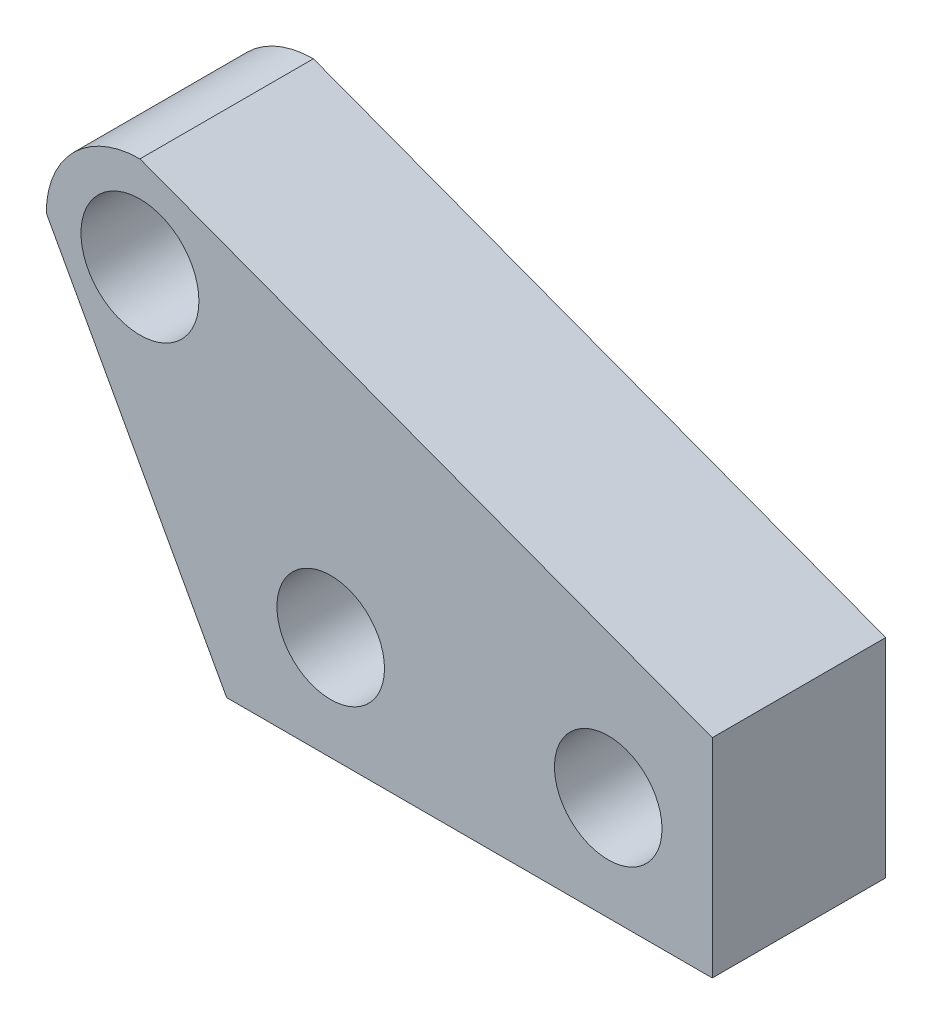
SolidWorks part; units mm, degrees
ref_plane "Front Plane" through (0, 0, 0) normal (0, 0, 1) x (1, 0, 0)
ref_plane "Top Plane" through (0, 0, 0) normal (0, 1, 0) x (1, 0, 0)
ref_plane "Right Plane" through (0, 0, 0) normal (1, 0, 0) x (0, 0, -1)
sketch "Sketch1" plane through (0, 0, 0) normal (0, 0, 1) x (1, 0, 0)
  line L0 (0, 0) -> (6351.4326, 0) construction
  line L1 (0, 0) -> (0, 6351.4326) construction
  line L2 (-9.5, 0) -> (-9.5, 50000) construction
  line L3 (7, 0) -> (7, 50000) construction
  line L4 (-7, 0) -> (-7, 50000) construction
  line L5 (-7, 3) -> (7, 3)
  line L6 (-7, -3) -> (7, -3)
  line L9 (0, 3) -> (7, 3)
  line L10 (7, -3) -> (7, 3)
  line L11 (-9.5, 9.2) -> (7, 3)
  line L12 (-12.2, 6.5) -> (-7, -3)
  circle A0 centre (4, 0) radius 1.55
  circle A1 centre (-4, 0) radius 1.55
  circle A2 centre (-9.5, 6.5) radius 1.7
  arc A4 (-9.5, 9.2) -> (-12.2, 6.5) centre (-9.5, 6.5) ccw
  dimension "D2" = 3.1
  dimension "D3" = 3.1
  dimension "D6" = 3.4
  dimension "D1" = 4
  dimension "D4" = 8
  dimension "D5" = 5.5
  dimension "D7" = 6.5
  dimension "D8" = 2.7
  dimension "D9" = 3
  dimension "D10" = 3
  dimension "D11" = 3
extrude "Boss-Extrude1" add sketch "Sketch1" along normal blind 5
